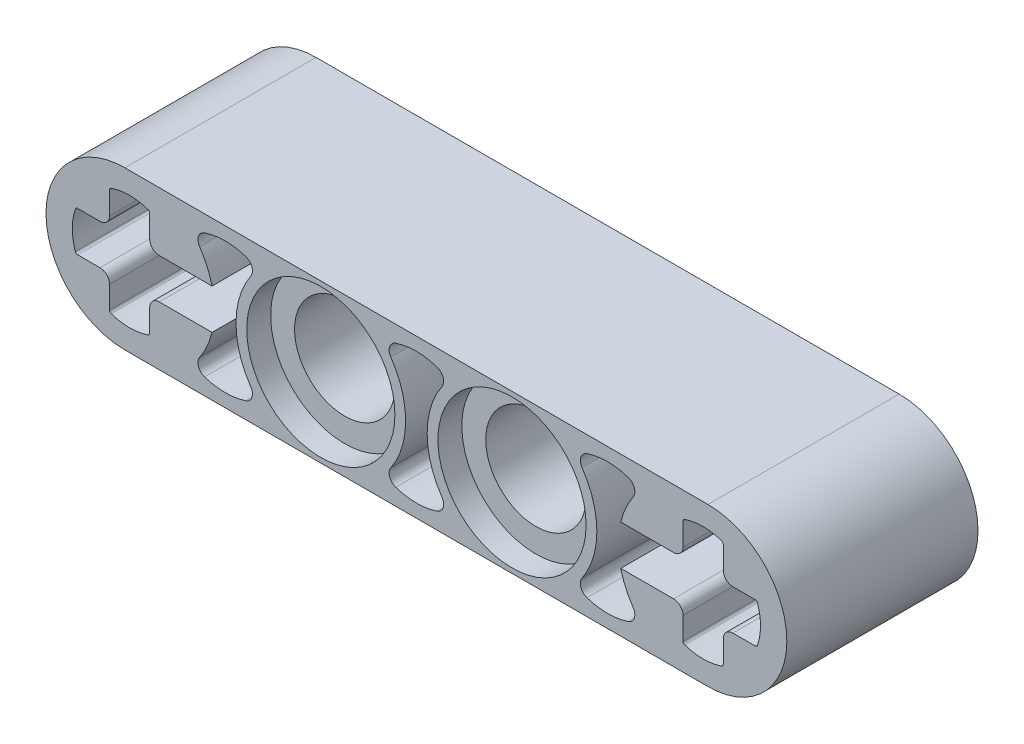
SolidWorks part; units mm, degrees
ref_plane "Front Plane" through (0, 0, 0) normal (0, 0, 1) x (1, 0, 0)
ref_plane "Top Plane" through (0, 0, 0) normal (0, 1, 0) x (1, 0, 0)
ref_plane "Right Plane" through (0, 0, 0) normal (1, 0, 0) x (0, 0, -1)
sketch "Sketch1" plane through (0, 0, 0) normal (0, 0, 1) x (1, 0, 0)
  line L14 (-13.24, 0.84) -> (-14.1777, 0.84)
  line L15 (-12.84, -2.1777) -> (-12.84, -1.24)
  line L16 (-11.16, -2.1777) -> (-11.16, -1.24)
  line L17 (-9.8223, 0.84) -> (-10.76, 0.84)
  line L18 (-9.8223, -0.84) -> (-10.76, -0.84)
  line L19 (-12.84, 1.24) -> (-12.84, 2.1777)
  line L20 (-11.16, 1.24) -> (-11.16, 2.1777)
  line L21 (-13.24, -0.84) -> (-14.1777, -0.84)
  line L22 (-9.7518, 0.84) -> (-8.5508, 0.84)
  line L23 (-9.7518, -0.84) -> (-8.5508, -0.84)
  line L24 (-9.8223, -0.84) -> (-9.7518, -0.84)
  line L25 (-9.8223, 0.84) -> (-9.7518, 0.84)
  line L26 (0, -55) -> (0, 55) construction
  line L27 (12.84, 1.24) -> (12.84, 2.1777)
  line L28 (11.16, 1.24) -> (11.16, 2.1777)
  line L29 (9.8223, 0.84) -> (10.76, 0.84)
  line L30 (9.8223, 0.84) -> (9.7518, 0.84)
  line L31 (9.7518, 0.84) -> (8.5508, 0.84)
  line L32 (9.7518, -0.84) -> (8.5508, -0.84)
  line L33 (9.8223, -0.84) -> (9.7518, -0.84)
  line L34 (9.8223, -0.84) -> (10.76, -0.84)
  line L35 (11.16, -2.1777) -> (11.16, -1.24)
  line L36 (12.84, -2.1777) -> (12.84, -1.24)
  line L37 (13.24, -0.84) -> (14.1777, -0.84)
  line L38 (13.24, 0.84) -> (14.1777, 0.84)
  line L44 (-12.2, 3.3) -> (12.2, 3.3)
  line L45 (-12.2, -3.3) -> (12.2, -3.3)
  circle A23 centre (-4, 0) radius 2.1
  arc A24 (-8.866, -2.6101) -> (-7.134, -2.6101) centre (-8, 0) ccw
  arc A25 (-6.9299, -2.0046) -> (-7.134, -2.6101) centre (-7.26, -2.2304) cw
  arc A26 (-6.9299, -2.0046) -> (-6.9299, 2.0046) centre (-4, 0) cw
  arc A27 (-6.9299, 2.0046) -> (-7.134, 2.6101) centre (-7.26, 2.2304) ccw
  arc A28 (-7.134, 2.6101) -> (-8.866, 2.6101) centre (-8, 0) ccw
  arc A29 (-9.0701, 2.0046) -> (-8.866, 2.6101) centre (-8.74, 2.2304) cw
  arc A30 (-9.0701, -2.0046) -> (-9.0701, 2.0046) centre (-12, 0) ccw
  arc A31 (-9.0701, -2.0046) -> (-8.866, -2.6101) centre (-8.74, -2.2304) ccw
  arc A32 (-11.2278, 2.2724) -> (-12.7722, 2.2724) centre (-12, 0) ccw
  arc A33 (-14.2724, 0.7722) -> (-14.2724, -0.7722) centre (-12, 0) ccw
  arc A34 (-12.7722, -2.2724) -> (-11.2278, -2.2724) centre (-12, 0) ccw
  arc A35 (-12.84, -1.24) -> (-13.24, -0.84) centre (-13.24, -1.24) ccw
  arc A36 (-11.16, -1.24) -> (-10.76, -0.84) centre (-10.76, -1.24) cw
  arc A37 (-10.76, 0.84) -> (-11.16, 1.24) centre (-10.76, 1.24) cw
  arc A38 (-13.24, 0.84) -> (-12.84, 1.24) centre (-13.24, 1.24) ccw
  arc A39 (-14.1777, 0.84) -> (-14.2724, 0.7722) centre (-14.1777, 0.74) ccw
  arc A40 (-14.1777, -0.84) -> (-14.2724, -0.7722) centre (-14.1777, -0.74) cw
  arc A41 (-12.7722, -2.2724) -> (-12.84, -2.1777) centre (-12.74, -2.1777) cw
  arc A42 (-11.2278, -2.2724) -> (-11.16, -2.1777) centre (-11.26, -2.1777) ccw
  arc A43 (-11.2278, 2.2724) -> (-11.16, 2.1777) centre (-11.26, 2.1777) cw
  arc A44 (-12.84, 2.1777) -> (-12.7722, 2.2724) centre (-12.74, 2.1777) cw
  arc A45 (-8.5508, -0.84) -> (-8.5508, 0.84) centre (-12, 0) ccw
  arc A46 (13.24, 0.84) -> (12.84, 1.24) centre (13.24, 1.24) cw
  arc A47 (12.84, 2.1777) -> (12.7722, 2.2724) centre (12.74, 2.1777) ccw
  arc A48 (11.2278, 2.2724) -> (12.7722, 2.2724) centre (12, 0) cw
  arc A49 (11.2278, 2.2724) -> (11.16, 2.1777) centre (11.26, 2.1777) ccw
  arc A50 (10.76, 0.84) -> (11.16, 1.24) centre (10.76, 1.24) ccw
  arc A51 (8.5508, -0.84) -> (8.5508, 0.84) centre (12, 0) cw
  arc A52 (11.16, -1.24) -> (10.76, -0.84) centre (10.76, -1.24) ccw
  arc A53 (11.2278, -2.2724) -> (11.16, -2.1777) centre (11.26, -2.1777) cw
  arc A54 (12.7722, -2.2724) -> (11.2278, -2.2724) centre (12, 0) cw
  arc A55 (12.7722, -2.2724) -> (12.84, -2.1777) centre (12.74, -2.1777) ccw
  arc A56 (12.84, -1.24) -> (13.24, -0.84) centre (13.24, -1.24) cw
  arc A57 (14.1777, -0.84) -> (14.2724, -0.7722) centre (14.1777, -0.74) ccw
  arc A58 (14.2724, 0.7722) -> (14.2724, -0.7722) centre (12, 0) cw
  arc A59 (14.1777, 0.84) -> (14.2724, 0.7722) centre (14.1777, 0.74) cw
  arc A60 (9.0701, -2.0046) -> (8.866, -2.6101) centre (8.74, -2.2304) cw
  arc A61 (9.0701, -2.0046) -> (9.0701, 2.0046) centre (12, 0) cw
  arc A62 (9.0701, 2.0046) -> (8.866, 2.6101) centre (8.74, 2.2304) ccw
  arc A63 (7.134, 2.6101) -> (8.866, 2.6101) centre (8, 0) cw
  arc A64 (6.9299, 2.0046) -> (7.134, 2.6101) centre (7.26, 2.2304) cw
  arc A65 (6.9299, -2.0046) -> (6.9299, 2.0046) centre (4, 0) ccw
  arc A66 (6.9299, -2.0046) -> (7.134, -2.6101) centre (7.26, -2.2304) ccw
  arc A67 (8.866, -2.6101) -> (7.134, -2.6101) centre (8, 0) cw
  circle A68 centre (4, 0) radius 2.1
  arc A73 (-12.2, 3.3) -> (-12.2, -3.3) centre (-12.2, 0) ccw
  arc A74 (12.2, 3.3) -> (12.2, -3.3) centre (12.2, 0) cw
  arc A75 (-0.866, -2.6101) -> (0.866, -2.6101) centre (0, 0) ccw
  arc A76 (1.0701, -2.0046) -> (0.866, -2.6101) centre (0.74, -2.2304) cw
  arc A77 (1.0701, -2.0046) -> (1.0701, 2.0046) centre (4, 0) cw
  arc A78 (1.0701, 2.0046) -> (0.866, 2.6101) centre (0.74, 2.2304) ccw
  arc A79 (0.866, 2.6101) -> (-0.866, 2.6101) centre (0, 0) ccw
  arc A80 (-1.0701, 2.0046) -> (-0.866, 2.6101) centre (-0.74, 2.2304) cw
  arc A81 (-1.0701, -2.0046) -> (-1.0701, 2.0046) centre (-4, 0) ccw
  arc A82 (-1.0701, -2.0046) -> (-0.866, -2.6101) centre (-0.74, -2.2304) ccw
  point P119 (0, 3.3)
  point P122 (0, -3.3)
  point P133 (0, 0)
  dimension "D2" = 4.2
  dimension "D3" = 4
extrude "Boss-Extrude1" add sketch "Sketch1" along normal mid plane 8 contours A74 L44 A73 L45 A82 A81 A80 A79 A78 A77 A76 A75 A60 A67 A66 A65 A64 A63 A62 A61 L31 L30 L29 A50 L28 A49 A48 A47 L27 A46 L38 A59 A58 A57 L37 A56 L36 A55 A54 A53 L35 A52 L34 L33 L32 L19 A44
sketch "Sketch2" plane through (0, 0, 4) normal (0, 0, 1) x (1, 0, 0)
  circle A0 centre (-4, 0) radius 3.1
  circle A1 centre (4, 0) radius 3.1
  dimension "D1" = 6.2
  dimension "D2" = 6.2
extrude "Cut-Extrude1" cut sketch "Sketch2" against normal blind 1
mirror "Mirror1" about plane through (0, 0, 0) normal (0, 0, 1) of "Cut-Extrude1"
